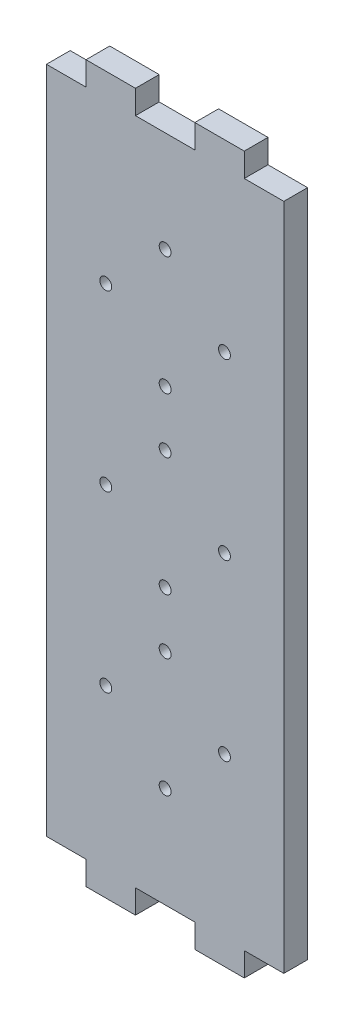
SolidWorks part; units mm, degrees
ref_plane "Alzado" through (0, 0, 0) normal (0, 0, 1) x (1, 0, 0)
ref_plane "Planta" through (0, 0, 0) normal (0, 1, 0) x (1, 0, 0)
ref_plane "Vista lateral" through (0, 0, 0) normal (1, 0, 0) x (0, 0, -1)
sketch "Sketch1" plane through (0, 0, 0) normal (0, 0, 1) x (1, 0, 0)
  line L0 (-15, 42.25) -> (-10, 42.25)
  line L1 (-10, 45.25) -> (-3.75, 45.25)
  line L2 (-15, 42.25) -> (-15, -42.25)
  line L3 (10, -42.25) -> (15, -42.25)
  line L4 (15, 42.25) -> (15, -42.25)
  line L5 (-15, 45.25) -> (15, -45.25) construction
  line L6 (-15, -45.25) -> (15, 45.25) construction
  line L7 (-10, 42.25) -> (-10, 45.25)
  line L8 (-3.75, 45.25) -> (-3.75, 42.25)
  line L9 (-3.75, 42.25) -> (3.75, 42.25)
  line L10 (3.75, 42.25) -> (3.75, 45.25)
  line L11 (10, 45.25) -> (10, 42.25)
  line L12 (10, 42.25) -> (15, 42.25)
  line L13 (0, 0) -> (0, 42.25) construction
  line L14 (3.75, 45.25) -> (10, 45.25)
  line L15 (-15, 42.25) -> (-15, 45.25) construction
  line L16 (-15, 45.25) -> (-10, 45.25) construction
  line L17 (15, 42.25) -> (15, 45.25) construction
  line L18 (15, 45.25) -> (10, 45.25) construction
  line L19 (0, 0) -> (15, 0) construction
  line L20 (10, -45.25) -> (10, -42.25)
  line L21 (3.75, -45.25) -> (10, -45.25)
  line L22 (3.75, -42.25) -> (3.75, -45.25)
  line L23 (-3.75, -42.25) -> (3.75, -42.25)
  line L24 (-3.75, -45.25) -> (-3.75, -42.25)
  line L25 (-10, -45.25) -> (-3.75, -45.25)
  line L26 (-10, -42.25) -> (-10, -45.25)
  line L27 (-15, -42.25) -> (-10, -42.25)
  line L28 (-15, -42.25) -> (-15, -45.25) construction
  line L29 (-15, -45.25) -> (-10, -45.25) construction
  line L30 (10, -45.25) -> (15, -45.25) construction
  line L31 (15, -45.25) -> (15, -42.25) construction
  line L32 (15, 22) -> (-15, 22) construction
  line L33 (-15, -22) -> (15, -22) construction
  circle A0 centre (0, 22) radius 7.5 construction
  circle A1 centre (0, 0) radius 7.5 construction
  circle A2 centre (0, -22) radius 7.5 construction
  circle A3 centre (0, 29.5) radius 0.75
  circle A4 centre (7.5, 22) radius 0.75
  circle A5 centre (0, 14.5) radius 0.75
  circle A6 centre (-7.5, 22) radius 0.75
  circle A7 centre (0, 7.5) radius 0.75
  circle A8 centre (-7.5, 0) radius 0.75
  circle A9 centre (0, -7.5) radius 0.75
  circle A10 centre (7.5, 0) radius 0.75
  circle A11 centre (0, -14.5) radius 0.75
  circle A12 centre (-7.5, -22) radius 0.75
  circle A13 centre (0, -29.5) radius 0.75
  circle A14 centre (7.5, -22) radius 0.75
  point P0 (0, 0)
  dimension "D9" = 15
  dimension "D10" = 1.5
  dimension "D1" = 90.5
  dimension "D2" = 30
  dimension "D3" = 7.5
  dimension "D4" = 5
  dimension "D5" = 5
  dimension "D6" = 3
  dimension "D7" = 22
  dimension "D8" = 22
extrude "Boss-Extrude1" add sketch "Sketch1" along normal blind 3
